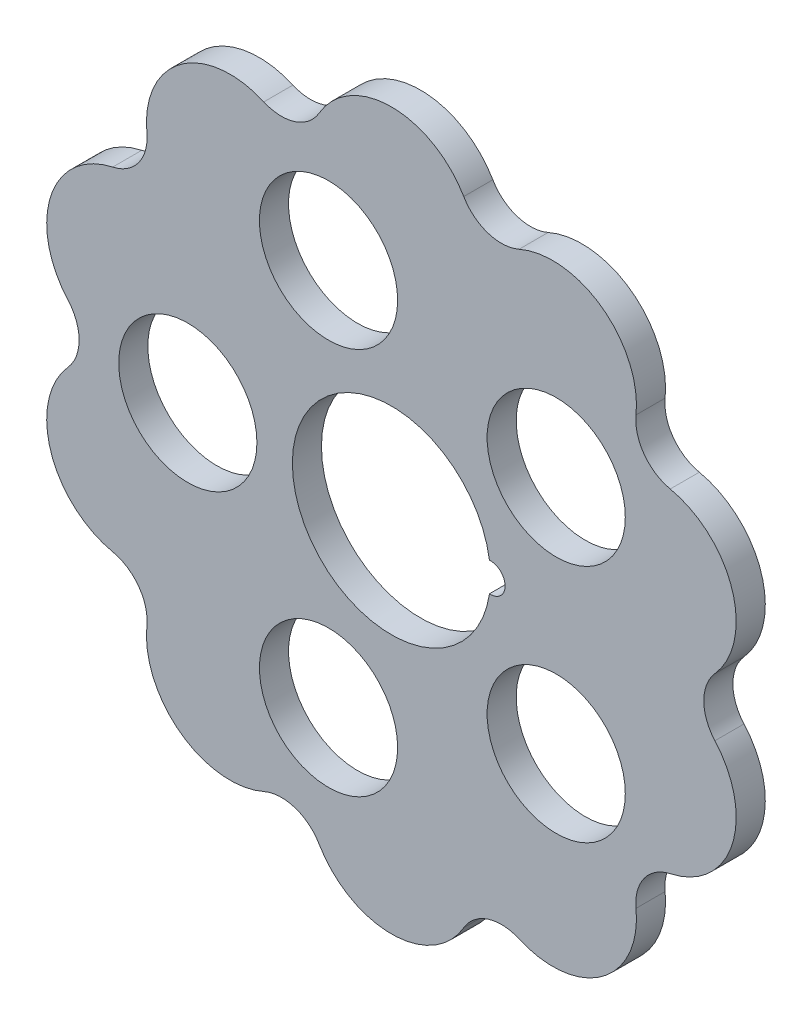
SolidWorks part; units mm, degrees
ref_plane "前视基准面" through (0, 0, 0) normal (0, 0, 1) x (1, 0, 0)
ref_plane "上视基准面" through (0, 0, 0) normal (0, 1, 0) x (1, 0, 0)
ref_plane "右视基准面" through (0, 0, 0) normal (1, 0, 0) x (0, 0, -1)
sketch "草图1" plane through (0, 0, 0) normal (0, 0, 1) x (1, 0, 0)
  line L0 (0, -30.9376) -> (22.1889, -23.728) construction
  line L1 (0, 6.8124) -> (11.0944, -27.3328) construction
  line L2 (11.0944, -27.3328) -> (15.711, -41.541) construction
  line L3 (0, 6.8124) -> (0, -56.846) construction
  line L4 (-15.1255, -39.7392) -> (0, -30.9376) construction
  line L5 (0, -30.9376) -> (15.1255, -39.7392) construction
  line L6 (-15.1255, -39.7392) -> (0, 6.8124) construction
  circle A0 centre (0, 6.8124) radius 13.625
  circle A1 centre (0, 6.8124) radius 28 construction
  circle A6 centre (26.6296, -1.8401) radius 9.5 construction
  circle A7 centre (0, 6.8124) radius 37.75 construction
  circle A8 centre (0, -30.9376) radius 11.5 construction
  circle A9 centre (-22.1889, -23.728) radius 11.5 construction
  circle A10 centre (-15.1255, -39.7392) radius 6 construction
  arc A11 (-9.9396, -36.7215) -> (9.9396, -36.7215) centre (0, -30.9376) ccw
  arc A12 (9.9396, -36.7215) -> (17.5473, -34.2497) centre (15.1255, -39.7392) cw
  arc A13 (-33.6299, -22.5649) -> (-17.5473, -34.2497) centre (-22.1889, -23.728) ccw
  arc A14 (-17.5473, -34.2497) -> (-9.9396, -36.7215) centre (-15.1255, -39.7392) cw
  arc A15 (-44.4747, 2.8128) -> (-38.3317, -16.0935) centre (-35.9024, -4.853) ccw
  arc A16 (-38.3317, -16.0935) -> (-33.6299, -22.5649) centre (-39.5992, -21.9581) cw
  circle A17 centre (22.1889, -23.728) radius 11.5 construction
  circle A18 centre (0, 6.8124) radius 42.61 construction
  circle A19 centre (15.1255, -39.7392) radius 6 construction
  arc A20 (-38.3317, 29.7183) -> (-44.4747, 10.8119) centre (-35.9024, 18.4778) ccw
  arc A21 (-44.4747, 10.8119) -> (-44.4747, 2.8128) centre (-48.9473, 6.8124) cw
  arc A22 (-17.5473, 47.8744) -> (-33.6299, 36.1897) centre (-22.1889, 37.3528) ccw
  arc A23 (-33.6299, 36.1897) -> (-38.3317, 29.7183) centre (-39.5992, 35.5829) cw
  arc A24 (9.9396, 50.3463) -> (-9.9396, 50.3463) centre (0, 44.5624) ccw
  arc A25 (-9.9396, 50.3463) -> (-17.5473, 47.8744) centre (-15.1255, 53.364) cw
  arc A26 (33.6299, 36.1897) -> (17.5473, 47.8744) centre (22.1889, 37.3528) ccw
  arc A27 (17.5473, 47.8744) -> (9.9396, 50.3463) centre (15.1255, 53.364) cw
  arc A28 (44.4747, 10.8119) -> (38.3317, 29.7183) centre (35.9024, 18.4778) ccw
  arc A29 (38.3317, 29.7183) -> (33.6299, 36.1897) centre (39.5992, 35.5829) cw
  arc A30 (38.3317, -16.0935) -> (44.4747, 2.8128) centre (35.9024, -4.853) ccw
  arc A31 (44.4747, 2.8128) -> (44.4747, 10.8119) centre (48.9473, 6.8124) cw
  arc A32 (17.5473, -34.2497) -> (33.6299, -22.5649) centre (22.1889, -23.728) ccw
  arc A33 (33.6299, -22.5649) -> (38.3317, -16.0935) centre (39.5992, -21.9581) cw
  circle A34 centre (-8.6525, -19.8172) radius 9.5
  circle A35 centre (-28, 6.8124) radius 9.5
  circle A36 centre (-8.6525, 33.442) radius 9.5
  circle A37 centre (22.6525, 23.2704) radius 9.5
  circle A38 centre (22.6525, -9.6456) radius 9.5
  dimension "D1" = 27.25
  dimension "D2" = 56
  dimension "D3" = 19
  dimension "D4" = 23
  dimension "D5" = 75.5
  dimension "D6" = 85.22
  dimension "D7" = 12
  dimension "D8" = 5
extrude "凸台-拉伸1" add sketch "草图1" along normal blind 4 contours A22 A23 A20 A21 A15 A16 A13 A14 A11 A12 A32 A33 A30 A31 A28 A29 A26 A27 A24 A25
sketch "草图2" plane through (0, 0, 4) normal (0, 0, 1) x (1, 0, 0)
  circle A0 centre (13.625, 6.8124) radius 2
  circle A1 centre (0, 6.8124) radius 13.625 construction
extrude "切除-拉伸1" cut sketch "草图2" against normal blind 4
